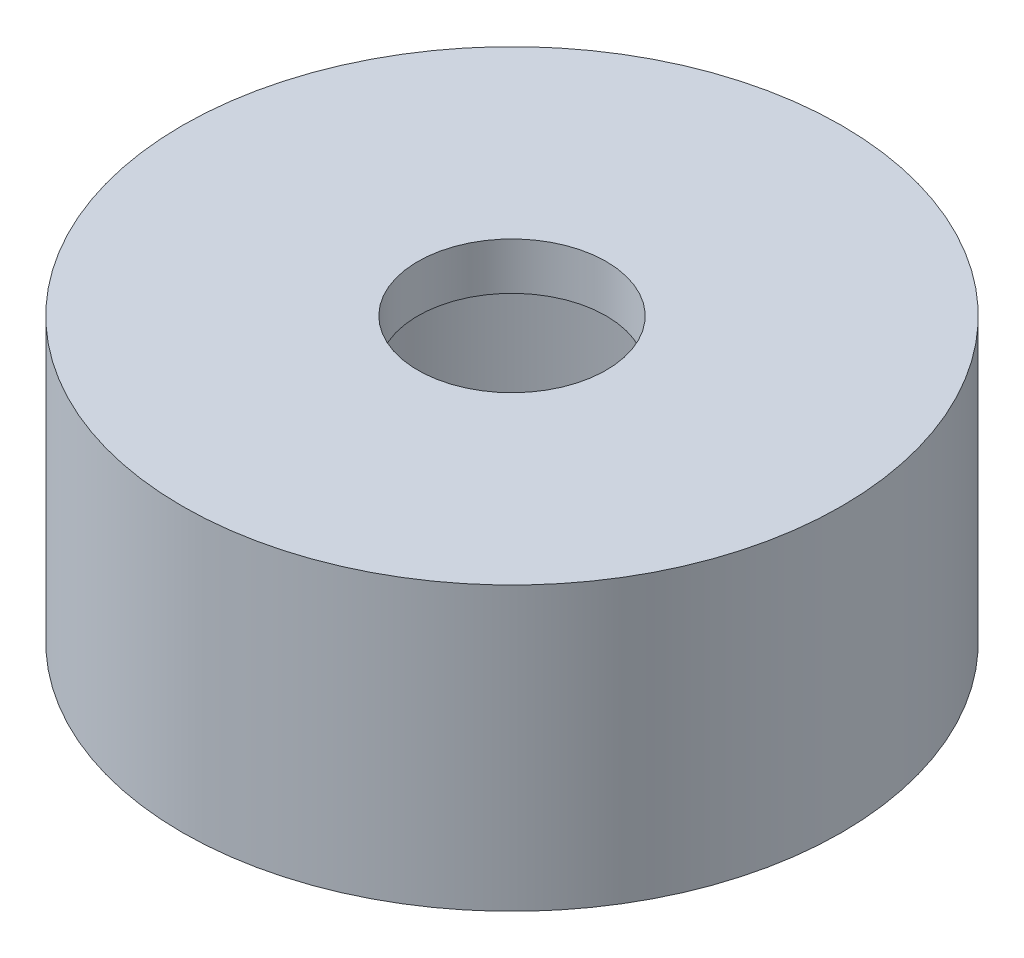
SolidWorks part; units mm, degrees
material "Acciaio al carbonio semplice"
ref_plane "Piano frontale" through (0, 0, 0) normal (0, 0, 1) x (1, 0, 0)
ref_plane "Piano superiore" through (0, 0, 0) normal (0, 1, 0) x (1, 0, 0)
ref_plane "Piano destro" through (0, 0, 0) normal (1, 0, 0) x (0, 0, -1)
sketch "Schizzo1" plane through (0, 0, 0) normal (0, 0, 1) x (1, 0, 0)
  line L0 (-12, 0) -> (-12, 10)
  line L1 (-12, 10) -> (-4, 10)
  line L2 (-4, 10) -> (-4, 12)
  line L3 (-4, 12) -> (-14, 12)
  line L4 (-14, 12) -> (-14, 0)
  line L5 (-14, 0) -> (-12, 0)
  line L6 (0, 0) -> (0, 28.5568) construction
  dimension "D1" = 24
  dimension "D2" = 28
  dimension "D3" = 10
  dimension "D4" = 12
  dimension "D5" = 8
revolve "Rivoluzione1" add sketch "Schizzo1" angle 360 about L6
